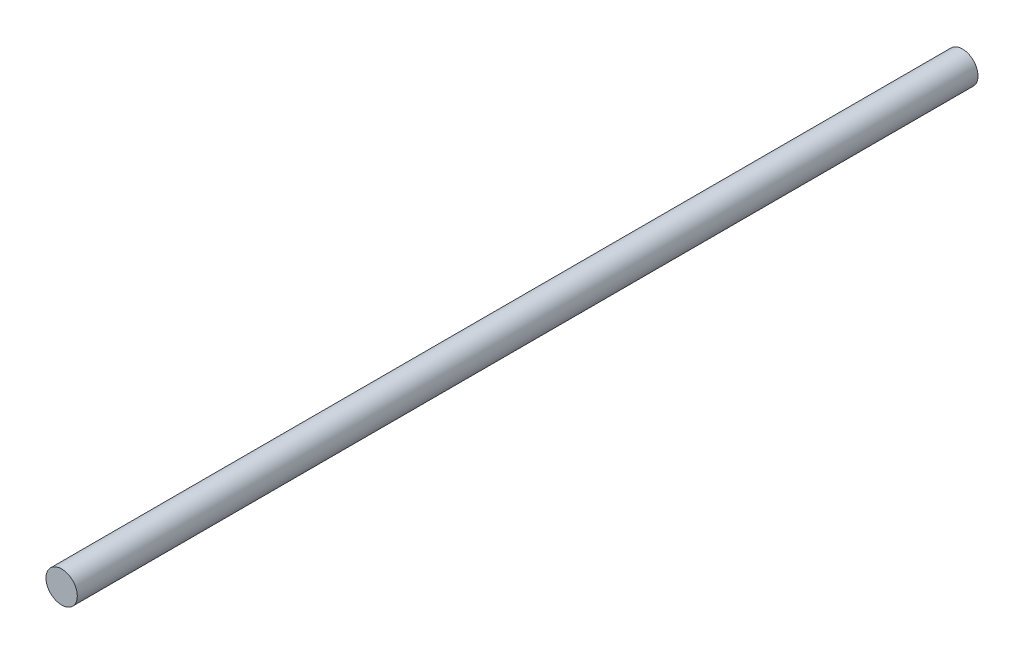
SolidWorks part; units mm, degrees
material "AISI 304"
ref_plane "Plano frontal" through (0, 0, 0) normal (0, 0, 1) x (1, 0, 0)
ref_plane "Plano superior" through (0, 0, 0) normal (0, 1, 0) x (1, 0, 0)
ref_plane "Plano direito" through (0, 0, 0) normal (1, 0, 0) x (0, 0, -1)
sketch "Esboço1" plane through (0, 0, 0) normal (0, 0, 1) x (1, 0, 0)
  circle A0 centre (0, 0) radius 4
  dimension "D1" = 8
extrude "Ressalto-extrusão1" add sketch "Esboço1" along normal blind 230
